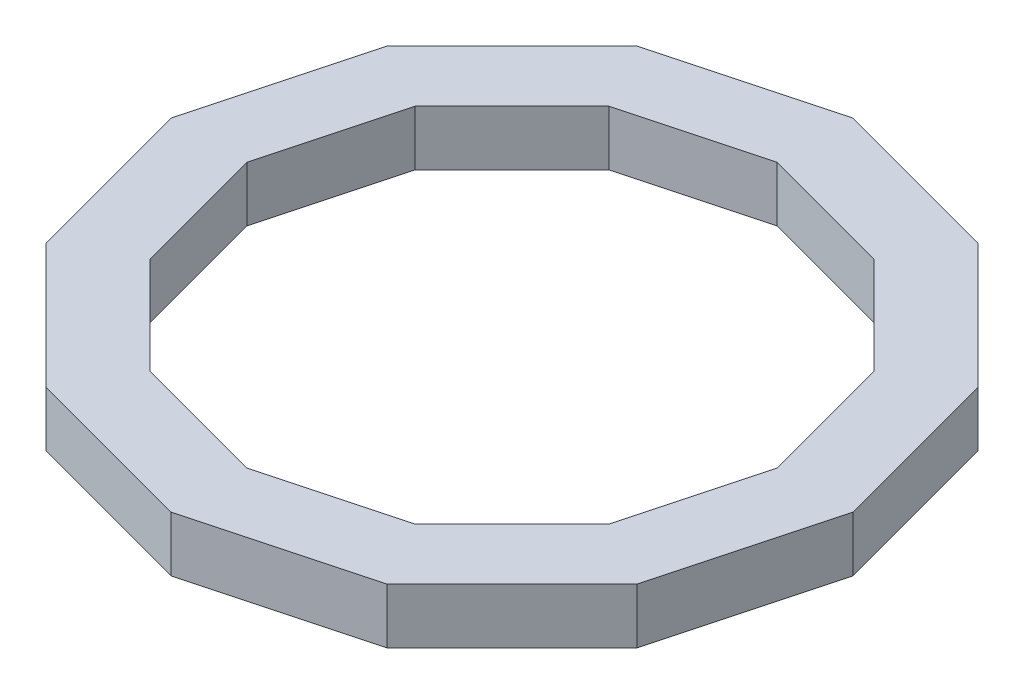
SolidWorks part; units mm, degrees
ref_plane "Front Plane" through (0, 0, 0) normal (0, 0, 1) x (1, 0, 0)
ref_plane "Top Plane" through (0, 0, 0) normal (0, 1, 0) x (1, 0, 0)
ref_plane "Right Plane" through (0, 0, 0) normal (1, 0, 0) x (0, 0, -1)
sketch "Sketch1" plane through (0, 0, 0) normal (0, 1, 0) x (1, 0, 0)
  line L0 (0, 0) -> (91.4697, 0) construction
  line L1 (117.7657, 0) -> (101.9881, 58.8828)
  line L2 (101.9881, 58.8828) -> (58.8828, 101.9881)
  line L3 (58.8828, 101.9881) -> (0, 117.7657)
  line L4 (0, 117.7657) -> (-58.8828, 101.9881)
  line L5 (-58.8828, 101.9881) -> (-101.9881, 58.8828)
  line L6 (-101.9881, 58.8828) -> (-117.7657, 0)
  line L7 (-117.7657, 0) -> (-101.9881, -58.8828)
  line L8 (-101.9881, -58.8828) -> (-58.8828, -101.9881)
  line L9 (-58.8828, -101.9881) -> (0, -117.7657)
  line L10 (0, -117.7657) -> (58.8828, -101.9881)
  line L11 (58.8828, -101.9881) -> (101.9881, -58.8828)
  line L12 (101.9881, -58.8828) -> (117.7657, 0)
  line L13 (91.4697, 0) -> (79.2151, 45.7348)
  line L14 (79.2151, 45.7348) -> (45.7348, 79.2151)
  line L15 (45.7348, 79.2151) -> (0, 91.4697)
  line L16 (0, 91.4697) -> (-45.7348, 79.2151)
  line L17 (-45.7348, 79.2151) -> (-79.2151, 45.7348)
  line L18 (-79.2151, 45.7348) -> (-91.4697, 0)
  line L19 (-91.4697, 0) -> (-79.2151, -45.7348)
  line L20 (-79.2151, -45.7348) -> (-45.7348, -79.2151)
  line L21 (-45.7348, -79.2151) -> (0, -91.4697)
  line L22 (0, -91.4697) -> (45.7348, -79.2151)
  line L23 (45.7348, -79.2151) -> (79.2151, -45.7348)
  line L24 (79.2151, -45.7348) -> (91.4697, 0)
  circle A0 centre (0, 0) radius 113.7529 construction
  circle A1 centre (0, 0) radius 88.3529 construction
  dimension "D1" = 25.4
  dimension "D2" = 60.96
extrude "Boss-Extrude1" add sketch "Sketch1" along normal blind 19.05
